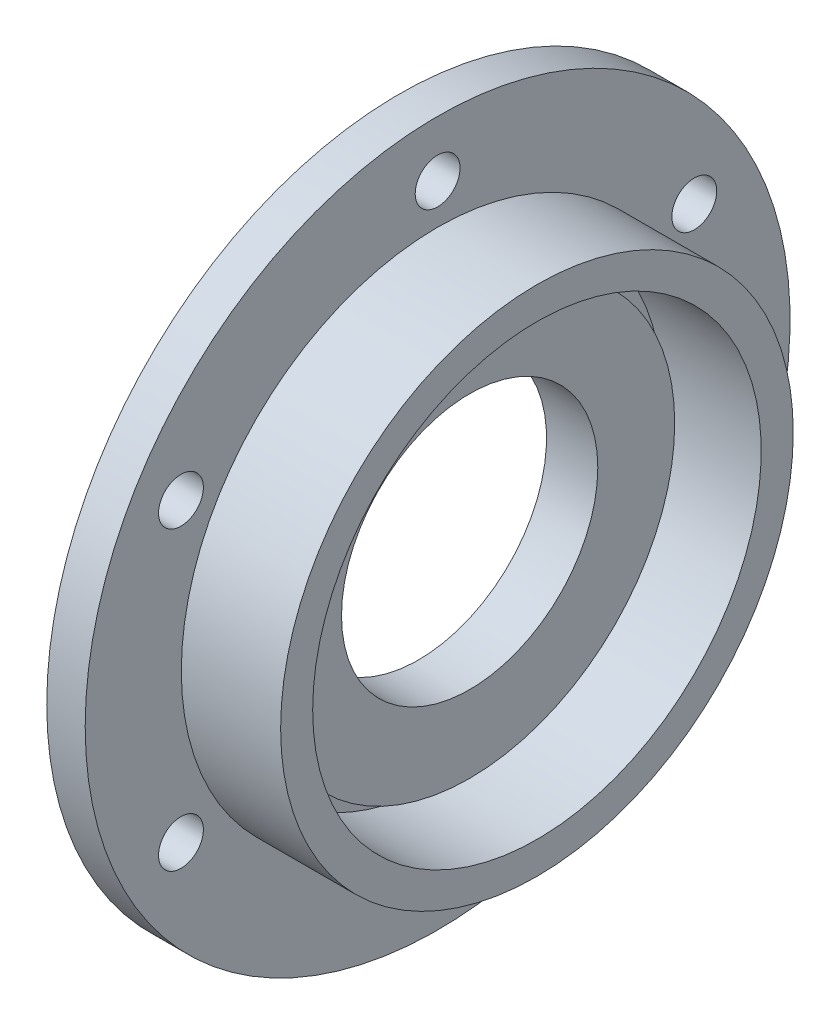
SolidWorks part; units mm, degrees
material "Plain Carbon Steel"
ref_plane "Front Plane" through (0, 0, 0) normal (0, 0, 1) x (1, 0, 0)
ref_plane "Top Plane" through (0, 0, 0) normal (0, 1, 0) x (1, 0, 0)
ref_plane "Right Plane" through (0, 0, 0) normal (1, 0, 0) x (0, 0, -1)
sketch "Sketch1" plane through (0, 0, 0) normal (0, 0, 1) x (1, 0, 0)
  line L0 (0, 0) -> (36.0745, 0) construction
  line L1 (0, 75) -> (0, 110)
  line L2 (0, 110) -> (12, 110)
  line L3 (12, 110) -> (12, 80)
  line L4 (12, 80) -> (43, 80)
  line L5 (43, 80) -> (43, 70)
  line L6 (43, 70) -> (12, 70)
  line L7 (12, 70) -> (12, 0)
  line L8 (12, 0) -> (6, 0)
  line L9 (6, 0) -> (6, 75)
  line L10 (6, 75) -> (0, 75)
  dimension "D1" = 12
  dimension "D2" = 43
  dimension "D3" = 6
  dimension "D4" = 150
  dimension "D5" = 220
  dimension "D6" = 160
  dimension "D7" = 140
revolve "Revolve1" add sketch "Sketch1" angle 360 about L0
sketch "Sketch2" plane through (0, 0, 0) normal (-1, 0, 0) x (0, 0, 1)
  circle A0 centre (0, 0) radius 92.5 construction
  circle A1 centre (0, 92.5) radius 7
  circle A2 centre (80.1073, 46.25) radius 7
  circle A3 centre (80.1073, -46.25) radius 7
  circle A4 centre (0, -92.5) radius 7
  circle A5 centre (-80.1073, -46.25) radius 7
  circle A6 centre (-80.1073, 46.25) radius 7
  point P17 (0, 0)
  dimension "D1" = 185
  dimension "D2" = 14
  dimension "D3" = 6
extrude "Cut-Extrude1" cut sketch "Sketch2" against normal up to surface (12 mm away) up to face at (12, 0, 110)
sketch "Sketch3" plane through (6, 0, 0) normal (-1, 0, 0) x (0, 0, 1)
  circle A0 centre (0, 0) radius 40
  dimension "D1" = 80
extrude "Cut-Extrude2" cut sketch "Sketch3" against normal up to surface (6 mm away) up to face at (12, 0, 70)
sketch "Sketch4" plane through (12, 0, 0) normal (1, 0, 0) x (0, 0, -1)
  circle A0 centre (0, 0) radius 40 construction
  circle A1 centre (0, 0) radius 40
  circle A2 centre (0, 0) radius 64
  dimension "D1" = 24
extrude "Boss-Extrude1" add sketch "Sketch4" along normal blind 10
